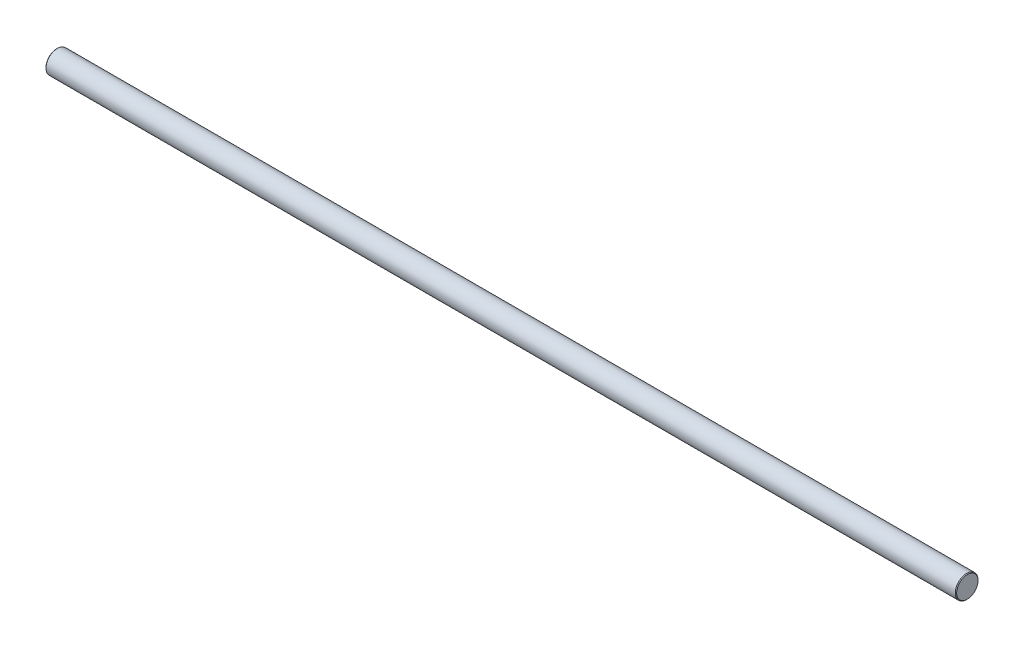
SolidWorks part; units mm, degrees
ref_plane "前基準面" through (0, 0, 0) normal (0, 0, 1) x (1, 0, 0)
ref_plane "上基準面" through (0, 0, 0) normal (0, 1, 0) x (1, 0, 0)
ref_plane "右基準面" through (0, 0, 0) normal (1, 0, 0) x (0, 0, -1)
ref_plane "平面1" through (0, 0, 0) normal (0, 0, 1) x (1, 0, 0)
sketch "草圖1" plane through (0, 0, 0) normal (0, 0, 1) x (1, 0, 0)
  line L0 (0, 0) -> (0, 7.5)
  line L1 (0, 7.5) -> (0.5, 8)
  line L2 (0.5, 8) -> (639.5, 8)
  line L3 (639.5, 8) -> (640, 7.5)
  line L4 (640, 7.5) -> (640, 0)
  line L5 (640, 0) -> (0, 0)
  line L6 (640, 0) -> (0, 0) construction
revolve "旋轉1" add sketch "草圖1" angle 360 about L6
